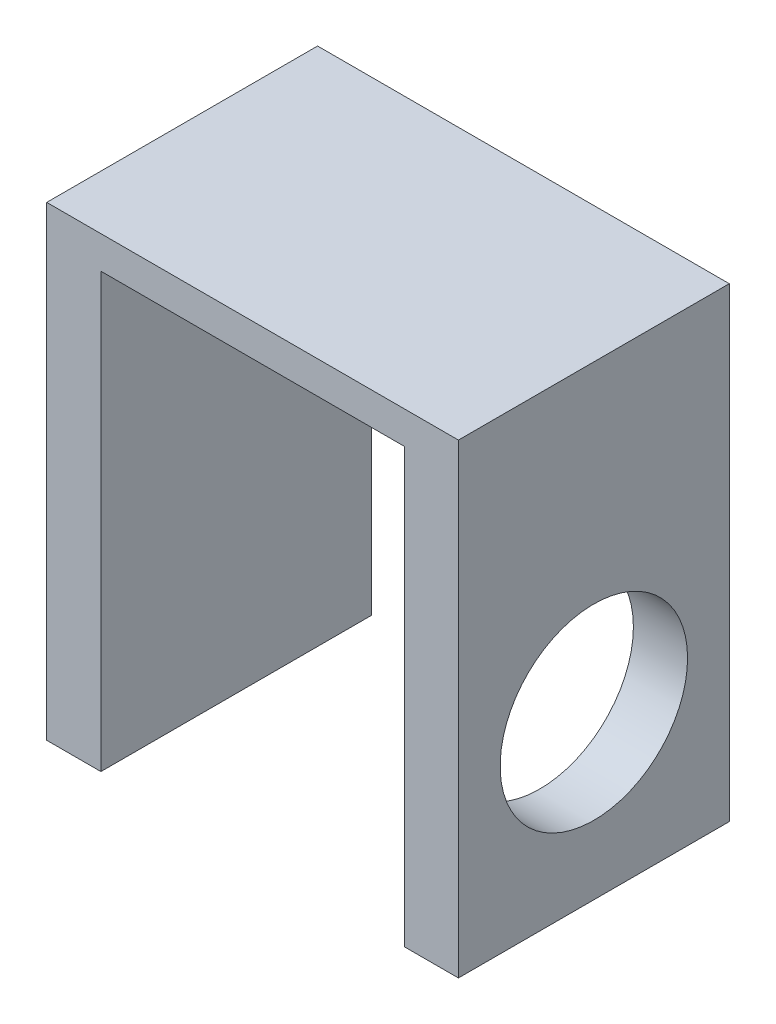
SolidWorks part; units mm, degrees
ref_plane "Front Plane" through (0, 0, 0) normal (0, 0, 1) x (1, 0, 0)
ref_plane "Top Plane" through (0, 0, 0) normal (0, 1, 0) x (1, 0, 0)
ref_plane "Right Plane" through (0, 0, 0) normal (1, 0, 0) x (0, 0, -1)
sketch "Sketch1" plane through (0, 0, 0) normal (0, 1, 0) x (1, 0, 0)
  line L1 (0, 0) -> (76, 0)
  line L2 (0, 0) -> (0, 50)
  line L3 (0, 50) -> (76, 50)
  line L4 (76, 0) -> (76, 50)
  dimension "D1" = 76
  dimension "D2" = 50
extrude "UAV Interface Top" add sketch "Sketch1" against normal blind 6
sketch "Sketch2" plane through (0, -6, 0) normal (0, -1, 0) x (1, 0, 0)
  line L0 (76, -50) -> (0, -50) construction
  line L1 (76, 0) -> (66, 0)
  line L2 (76, 0) -> (76, -50)
  line L3 (76, -50) -> (66, -50)
  line L4 (66, 0) -> (66, -50)
  dimension "D1" = 10
extrude "Spool and Motor Inserts" add sketch "Sketch2" along normal blind 80
ref_plane "Mirror Plane" through (38, 0, 0) normal (1, 0, 0) x (0, 0, -1)
mirror "Mirror1" about plane through (38, 0, 0) normal (1, 0, 0) of bodies 102 103
sketch "Sketch3" plane through (76, 0, 0) normal (1, 0, 0) x (0, 0, -1)
  line L0 (50, -86) -> (0, -86) construction
  circle A0 centre (25, -56) radius 17.3
  point P6 (25, -86)
  dimension "D1" = 34.6
  dimension "D2" = 30
extrude "Motor Cutout" cut sketch "Sketch3" against normal blind 30 contours A0
